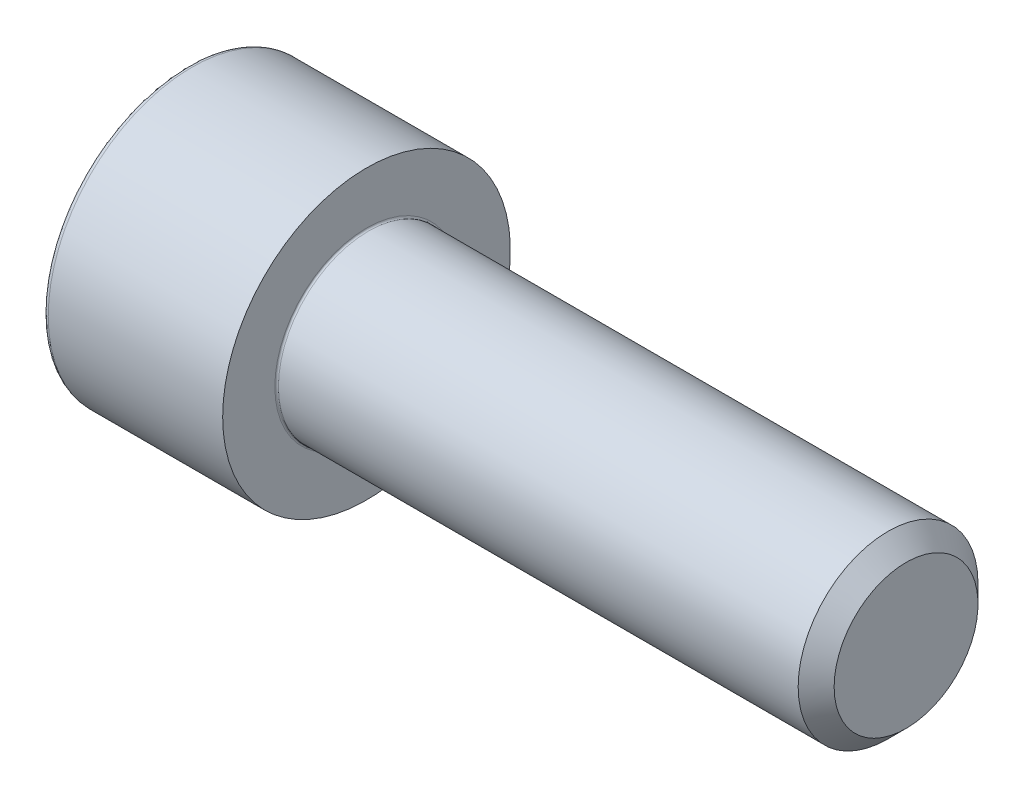
SolidWorks part; units mm, degrees
revolve "Base-Revolve" add sketch "BodySke"
sketch "BodySke" plane through (0, 0, 0) normal (0, 0, 1) x (1, 0, 0)
  line L0 (0, 0) -> (0, 8)
  line L1 (0, 8) -> (10, 8)
  line L2 (10, 8) -> (10, 5)
  line L3 (10, 5) -> (39, 5)
  line L4 (40, 4) -> (40, 0)
  line L5 (40, 0) -> (0, 0)
  line L6 (-31.75, 0) -> (127, 0) construction
  line L8 (40, 4) -> (39, 5)
  line L10 (40, -4) -> (39, -5) construction
  line L11 (10.5, 9.525) -> (10.5, 3.175) construction
  line L12 (30, 9.525) -> (30, 3.175) construction
  line L13 (24.0069, 9.525) -> (24.0069, 3.175) construction
  dimension "Head_ht" = 10
  dimension "Length" = 30
  dimension "Body_ch_ang" = 45
  dimension "Diameter" = 10
  dimension "Minor_dia" = 8
  dimension "Advance" = 0.5
  dimension "Thread_nom" = 10
  dimension "Thread_length" = 15.9931
  dimension "Head_dia" = 16
cosmetic thread "ThreadCosmetic" [suppressed]
fillet "Fillet1" radius 0.1 1 edges at (10, 0, 5)
fillet "Fillet2" radius 0.3 1 edges at (0, 0, 8)
ref_plane "Plane1" through (0, 0, 0) normal (0, 0, 1) x (1, 0, 0)
ref_plane "Plane2" through (0, 0, 0) normal (0, 1, 0) x (1, 0, 0)
ref_plane "Plane3" through (0, 0, 0) normal (1, 0, 0) x (0, 0, -1)
sketch "Sketch2" plane through (0, 0, 0) normal (0, 0, 1) x (1, 0, 0)
  line L0 (0, 4) -> (1.3, 4)
  line L1 (1.3, 4) -> (3.6094, 0)
  line L2 (-31.75, 0) -> (127, 0) construction
  line L3 (3.6094, 0) -> (0, 0)
  line L4 (0, 0) -> (0, 4)
  line L6 (0, 0) -> (47.625, 0) construction
  dimension "D1" = 4
  dimension "D2" = 60
  dimension "Depth" = 1.3
revolve "Hex-PreBroach" cut sketch "Sketch2" angle 360 about L6
sketch "Sketch3" plane through (0, 0, 0) normal (-1, 0, 0) x (0, 0.5, 0.866)
  line L0 (2.3094, 4) -> (-2.3094, 4)
  line L1 (-2.3094, 4) -> (-4.6188, 0)
  line L2 (2.3094, 4) -> (4.6188, 0)
  line L3 (2.3094, -4) -> (4.6188, 0)
  line L4 (2.3094, -4) -> (-2.3094, -4)
  line L5 (-2.3094, -4) -> (-4.6188, 0)
  dimension "D1" = 4
  dimension "D2" = 4
  dimension "Hex_size" = 8
extrude "Hex" cut sketch "Sketch3" against normal blind 1.3
sketch "ThdSchSke" plane through (0, 0, 0) normal (0, 0, 1) x (1, 0, 0)
  line L0 (30, -4) -> (29.2998, -5)
  line L1 (30, -4) -> (30.7002, -5)
  line L2 (30.7002, -5) -> (30.7002, -6.25)
  line L3 (-3.175, 0) -> (5.1513, 0) construction
  line L4 (0, 7.7) -> (0, -7.7) construction
  line L5 (30.7002, -6.25) -> (29.2998, -6.25)
  line L6 (29.2998, -6.25) -> (29.2998, -5)
  dimension "Thread_minor" = 8
  dimension "Diameter" = 10
  dimension "Start" = 30
revolve "ThreadSchematic" [suppressed] cut sketch "ThdSchSke" angle 360 about L3
pattern_linear "ThdSchPat" [suppressed]
equation "\"D2@Sketch3\" = \"Hex_size@Sketch3\" / 2"
equation "\"D1@Sketch3\" = \"Hex_size@Sketch3\" / 2"
equation "\"D1@Sketch2\" = \"Hex_size@Sketch3\" / 2"
equation "\"Thread_minor@ThreadCosmetic\"  =  \"Minor_dia@BodySke\""
equation "\"Depth@Sketch2\" =  \"Key_eng@Hex\""
equation "\"Thread_length@ThreadCosmetic\" = ((sgn( (\"Length@BodySke\" - \"Advance@BodySke\" * 3.0) - \"Thread_nom@BodySke\" )-1)*( (\"Length@BodySke\" - \"Advance@BodySke\" * 3.0) - \"Thread_nom@BodySke\" ))/-2+ \"Thread_nom@BodySke\""
equation "\"Thread_minor@ThdSchSke\" = \"Minor_dia@BodySke\""
equation "\"Diameter@ThdSchSke\" = \"Diameter@BodySke\""
equation "\"Overcut@ThdSchSke\" = \"Diameter@BodySke\" * 1.25"
equation "\"Start@ThdSchSke\" = \"Head_ht@BodySke\" + \"Length@BodySke\" - \"Thread_length@ThreadCosmetic\"  '---Non-countersunk---"
equation "\"Num_threads@ThdSchPat\" = int( \"Thread_length@ThreadCosmetic\" / \"Advance@BodySke\" + 0.999 )  + 1"
equation "\"Advance@ThdSchPat\" = \"Thread_length@ThreadCosmetic\" /  (\"Num_threads@ThdSchPat\" - 1) 'relax it"
equation "\"Num_threads@ThdSchPat\" = \"Num_threads@ThdSchPat\" - sgn( \"Num_threads@ThdSchPat\" - 1) '---chamfered tips only---"
